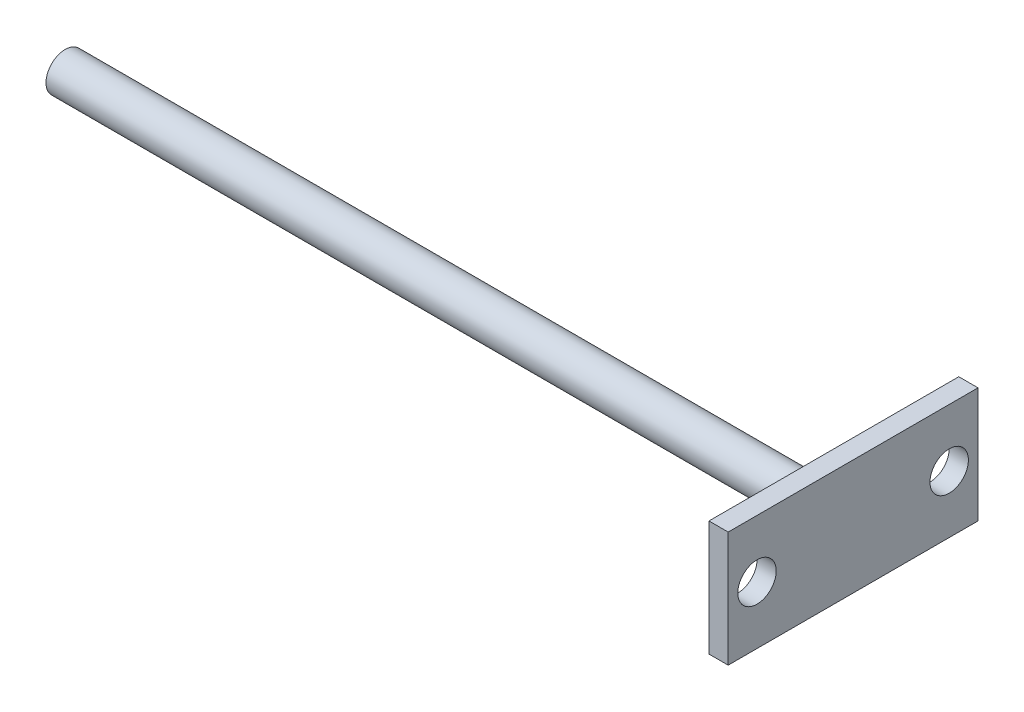
SolidWorks part; units mm, degrees
ref_plane "前视基准面" through (0, 0, 0) normal (0, 0, 1) x (1, 0, 0)
ref_plane "上视基准面" through (0, 0, 0) normal (0, 1, 0) x (1, 0, 0)
ref_plane "右视基准面" through (0, 0, 0) normal (1, 0, 0) x (0, 0, -1)
sketch "草图1" plane through (0, 0, 0) normal (0, 0, 1) x (1, 0, 0)
  line L1 (-2, 3) -> (2, 3)
  line L2 (-2, 3) -> (-2, -3)
  line L3 (-2, -3) -> (2, -3)
  line L4 (2, 3) -> (2, -3)
  line L5 (-2, 3) -> (2, -3) construction
  line L6 (-2, -3) -> (2, 3) construction
  circle A0 centre (0, 0) radius 1
  point P0 (0, 0)
  dimension "D3" = 2
  dimension "D1" = 4
  dimension "D2" = 6
extrude "凸台-拉伸1" add sketch "草图1" along normal blind 1
sketch "草图2" plane through (2, 0, 0) normal (1, 0, 0) x (0, 0, -1)
  line L0 (-4, 3) -> (-1, 3)
  line L1 (-4, 3) -> (-4, -3)
  line L2 (-4, -3) -> (-1, -3)
  line L3 (-1, -3) -> (-1, 3)
  line L4 (-1, 3) -> (2.5, 3)
  line L5 (-1, -3) -> (2.5, -3)
  line L6 (2.5, -3) -> (2.5, 3)
  circle A0 centre (-2.5, 0) radius 1
  line M6 (0, -3) -> (0, 3)
  line M7 (0, 3) -> (-1, 3)
  line M8 (-1, 3) -> (-1, -3)
  line M9 (-1, -3) -> (0, -3)
  dimension "D4" = 2
  dimension "D1" = 3
  dimension "D2" = 6
  dimension "D3" = 3.5
extrude "凸台-拉伸2" add sketch "草图2" along normal blind 1 contours L1 L2 L0 M8 | L5 L6 L4 M6 | M9 M6 M7 M8
fillet "圆角1" radius 1 2 edges at (-2, -3, 0.5) (-2, 3, 0.5)
mirror "镜向1" about plane through (3, 0, -2.5) normal (0, 0, 1) of bodies 107
sketch "草图3" plane through (2, 0, 0) normal (-1, 0, 0) x (0, 0, 1)
  line L1 (-6.6625, -3.802) -> (1.6625, -3.802)
  line L2 (-6.6625, -3.802) -> (-6.6625, 3.802)
  line L3 (-6.6625, 3.802) -> (1.6625, 3.802)
  line L4 (1.6625, -3.802) -> (1.6625, 3.802)
  line L5 (-6.6625, -3.802) -> (1.6625, 3.802) construction
  line L6 (-6.6625, 3.802) -> (1.6625, -3.802) construction
  point P0 (-2.5, 0)
extrude "切除-拉伸1" cut sketch "草图3" along normal blind 10
sketch "草图4" plane through (2, 0, 0) normal (-1, 0, 0) x (0, 0, 1)
  line L0 (-2.5, 3) -> (-2.5, -3)
  line L1 (4, 3) -> (-9, 3) construction
  line L2 (4, -3) -> (-9, -3) construction
  line L3 (-9, 0) -> (4, 0)
  line L4 (-9, 3) -> (-9, -3) construction
  line L5 (4, 3) -> (4, -3) construction
  circle A0 centre (-2.5, 0) radius 1
  dimension "D1" = 2
extrude "凸台-拉伸3" add sketch "草图4" along normal blind 40 contours L3 A0 L0 | L0 A0 L3 | L3 A0 L0 | L0 A0 L3
